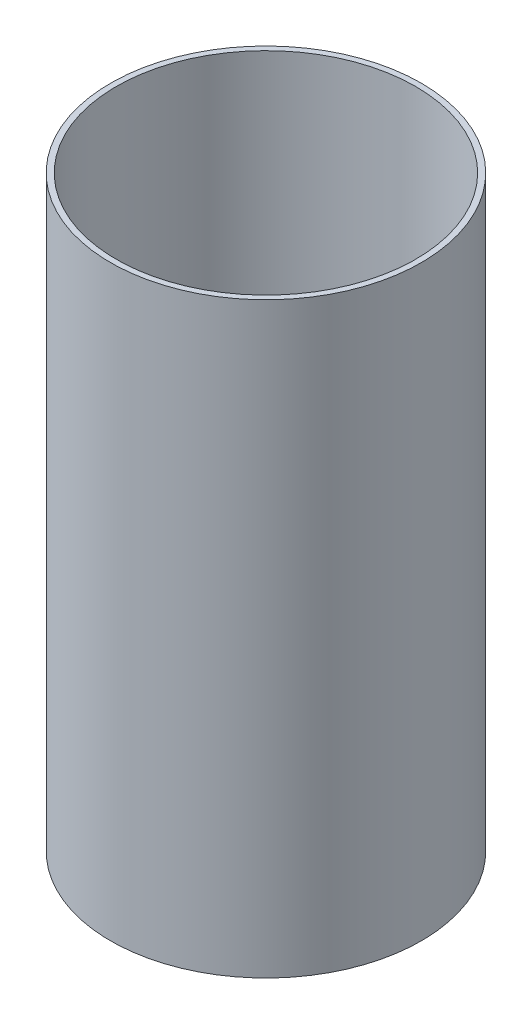
SolidWorks part; units mm, degrees
material "6063-T6"
ref_plane "Front Plane" through (0, 0, 0) normal (0, 0, 1) x (1, 0, 0)
ref_plane "Top Plane" through (0, 0, 0) normal (0, 1, 0) x (1, 0, 0)
ref_plane "Right Plane" through (0, 0, 0) normal (1, 0, 0) x (0, 0, -1)
sketch "Sketch1" plane through (0, 0, 0) normal (0, 1, 0) x (1, 0, 0)
  circle A0 centre (0, 0) radius 42.82
  circle A1 centre (0, 0) radius 44.45
  dimension "D1" = 88.9
  dimension "D2" = 1.63
extrude "Boss-Extrude1" add sketch "Sketch1" along normal blind 168
